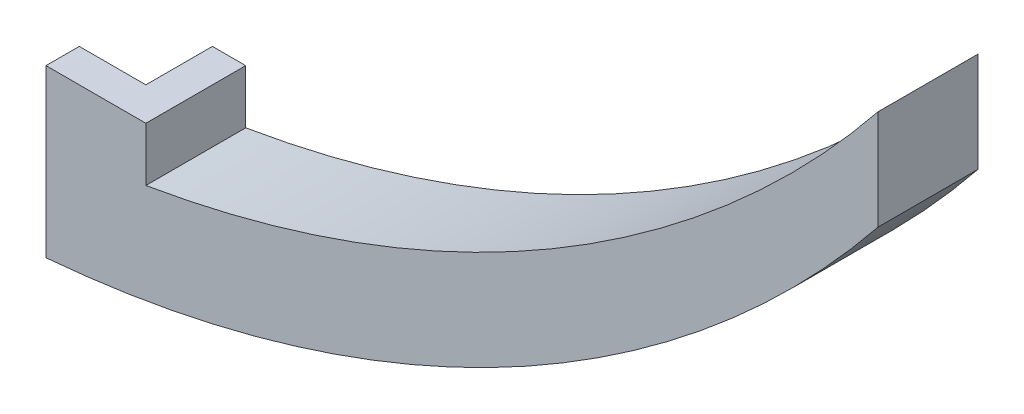
SolidWorks part; units mm, degrees
ref_plane "Ebene vorne" through (0, 0, 0) normal (0, 0, 1) x (1, 0, 0)
ref_plane "Ebene oben" through (0, 0, 0) normal (0, 1, 0) x (1, 0, 0)
ref_plane "Ebene rechts" through (0, 0, 0) normal (1, 0, 0) x (0, 0, -1)
sketch "Skizze1" plane through (0, 0, 0) normal (0, 0, 1) x (1, 0, 0)
  line L0 (0, 0) -> (0, 30)
  line L1 (250, 133.0037) -> (250, 163.0037)
  arc A0 (0, 0) -> (250, 133.0037) centre (-30.2937, 358.3993) ccw
  arc A1 (0, 30) -> (250, 163.0037) centre (-30.2937, 388.3993) ccw
  point P7 (250, 142.2557)
  point P8 (250, 121.4333)
  point P9 (250, 140.5606)
  point P10 (250, 133.0037)
  dimension "D1" = 30
  dimension "D2" = 30
  dimension "D3" = 250
extrude "Aufsatz-Linear austragen1" add sketch "Skizze1" along normal blind 30
ref_plane "Ebene1" through (0, 30, 0) normal (0, 1, 0) x (1, 0, 0)
sketch "Skizze2" plane through (0, 30, 0) normal (0, 1, 0) x (1, 0, 0)
  line L0 (0, 0) -> (0, -20)
  line L1 (0, -30) -> (0, 0) construction
  line L2 (0, -20) -> (20, -20)
  line L3 (20, -20) -> (20, 0)
  line L4 (250, 0) -> (0, 0) construction
  line L5 (20, 0) -> (0, 0)
  dimension "D1" = 20
  dimension "D2" = 20
extrude "Schnitt-Linear austragen1" cut sketch "Skizze2" along normal blind 10
sketch "Skizze3" plane through (0, 0, 30) normal (0, 0, 1) x (1, 0, 0)
  line L0 (0, 30) -> (0, 50)
  line L1 (0, 50) -> (20, 50)
  line L2 (20, 50) -> (20, 30)
  line L3 (20, 30) -> (0, 30)
  dimension "D1" = 20
  dimension "D2" = 20
extrude "Aufsatz-Linear austragen2" add sketch "Skizze3" against normal blind 10
sketch "Skizze4" plane through (20, 0, 0) normal (-1, 0, 0) x (0, 0, 1)
  line L0 (0, 32.2556) -> (30, 32.2556)
  line L1 (30, 32.2556) -> (30, 50)
  line L2 (30, 50) -> (0, 50)
  line L3 (0, 163.0037) -> (0, 32.2556) construction
  line L4 (0, 50) -> (0, 32.2556)
extrude "Aufsatz-Linear austragen4" add sketch "Skizze4" against normal blind 10
